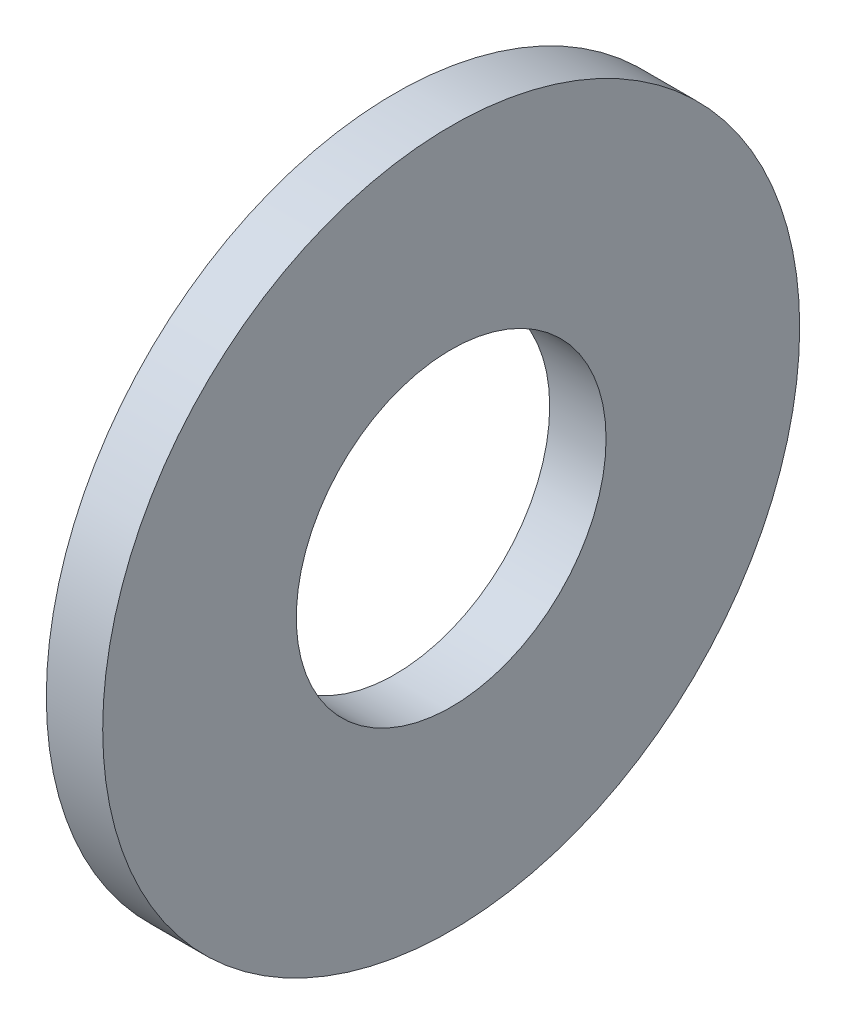
SolidWorks part; units mm, degrees
ref_plane "Front Plane" through (0, 0, 0) normal (0, 0, 1) x (1, 0, 0)
ref_plane "Top Plane" through (0, 0, 0) normal (0, 1, 0) x (1, 0, 0)
ref_plane "Right Plane" through (0, 0, 0) normal (1, 0, 0) x (0, 0, -1)
sketch "Sketch1" plane through (0, 0, 0) normal (1, 0, 0) x (0, 0, -1)
  circle A0 centre (0, 0) radius 14.2875
  circle A1 centre (0, 0) radius 6.35
  dimension "OD" = 28.575
  dimension "ID" = 12.7
extrude "Boss-Extrude1" add sketch "Sketch1" along normal blind 2.3114
